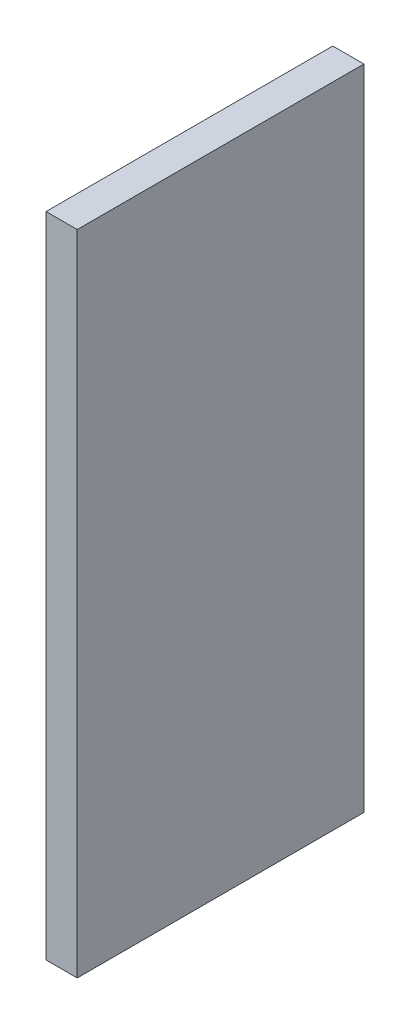
SolidWorks part; units mm, degrees
ref_plane "Front Plane" through (0, 0, 0) normal (0, 0, 1) x (1, 0, 0)
ref_plane "Top Plane" through (0, 0, 0) normal (0, 1, 0) x (1, 0, 0)
ref_plane "Right Plane" through (0, 0, 0) normal (1, 0, 0) x (0, 0, -1)
sketch "草圖1" plane through (0, 0, 0) normal (0, 0, 1) x (1, 0, 0)
  line L0 (-1.25, -26) -> (1.25, -26)
  line L1 (1.25, -26) -> (1.25, 26)
  line L2 (1.25, 26) -> (-1.25, 26)
  line L3 (-1.25, 26) -> (-1.25, -26)
extrude "填料-伸長1" add sketch "草圖1" along normal blind 23
